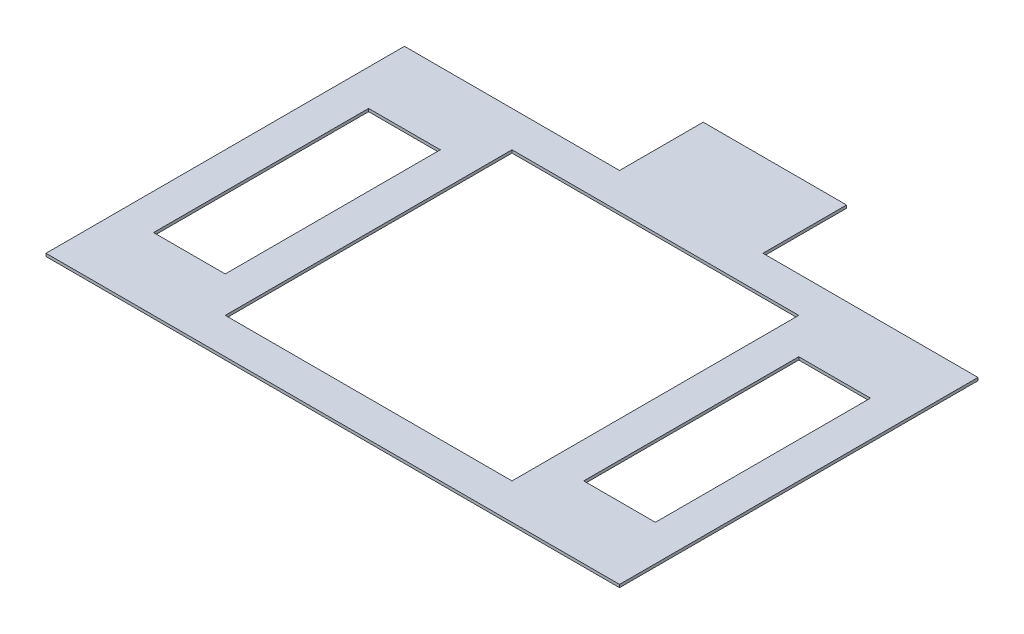
SolidWorks part; units mm, degrees
ref_plane "Front Plane" through (0, 0, 0) normal (0, 0, 1) x (1, 0, 0)
ref_plane "Top Plane" through (0, 0, 0) normal (0, 1, 0) x (1, 0, 0)
ref_plane "Right Plane" through (0, 0, 0) normal (1, 0, 0) x (0, 0, -1)
sketch "Sketch1" plane through (0, 0, 0) normal (0, 1, 0) x (1, 0, 0)
  line L0 (0, 0) -> (0, 375)
  line L1 (0, 375) -> (225, 375)
  line L2 (225, 375) -> (225, 462.5)
  line L3 (225, 462.5) -> (375, 462.5)
  line L4 (375, 462.5) -> (375, 375)
  line L5 (375, 375) -> (600, 375)
  line L6 (600, 375) -> (600, 0)
  line L7 (600, 0) -> (0, 0)
  line L9 (150, 337.5) -> (450, 337.5)
  line L10 (150, 337.5) -> (150, 37.5)
  line L11 (150, 37.5) -> (450, 37.5)
  line L12 (450, 337.5) -> (450, 37.5)
  line L13 (37.5, 300) -> (112.5, 300)
  line L14 (37.5, 300) -> (37.5, 75)
  line L15 (37.5, 75) -> (112.5, 75)
  line L16 (112.5, 300) -> (112.5, 75)
  line L17 (487.5, 300) -> (562.5, 300)
  line L18 (487.5, 300) -> (487.5, 75)
  line L19 (487.5, 75) -> (562.5, 75)
  line L20 (562.5, 300) -> (562.5, 75)
  point P5 (300, 462.5)
  point P10 (300, 0)
  point P23 (300, 337.5)
  point P24 (562.5, 187.5)
  point P25 (450, 187.5)
  point P26 (112.5, 187.5)
  point P27 (600, 187.5)
  dimension "D1" = 600
  dimension "D2" = 375
  dimension "D3" = 150
  dimension "D4" = 87.5
  dimension "D5" = 300
  dimension "D6" = 300
  dimension "D7" = 75
  dimension "D8" = 37.5
  dimension "D9" = 225
  dimension "D10" = 37.5
  dimension "D11" = 75
  dimension "D12" = 225
extrude "Boss-Extrude1" add sketch "Sketch1" along normal blind 3
